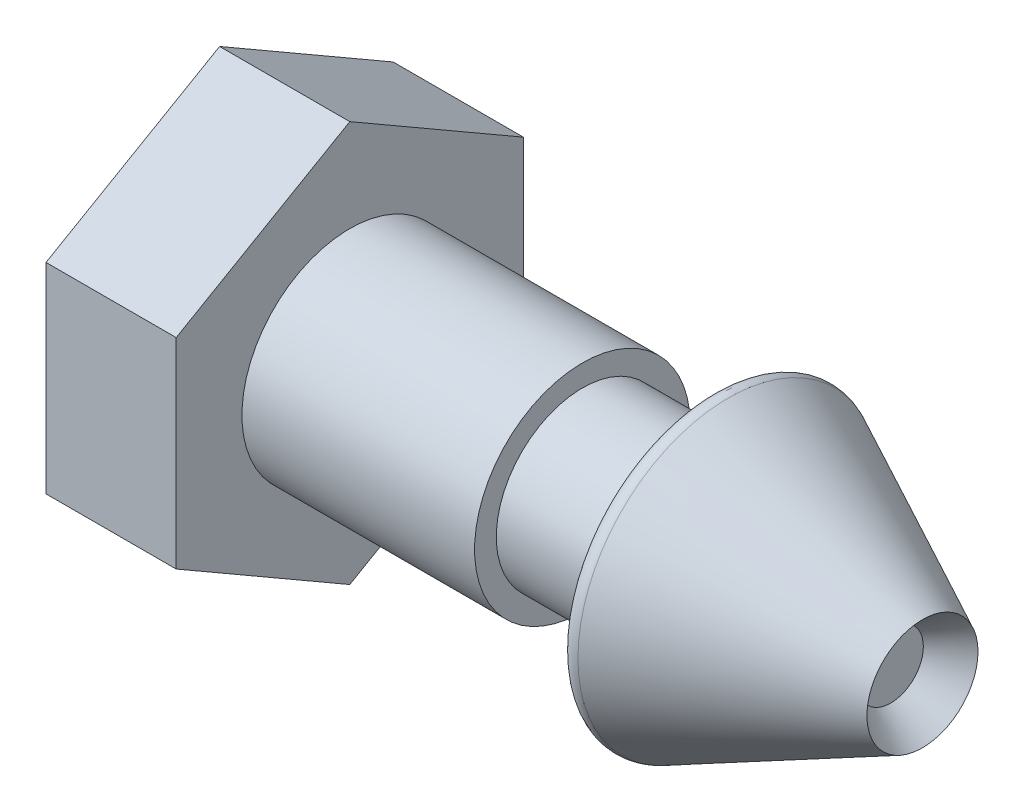
SolidWorks part; units mm, degrees
ref_plane "Front Plane" through (0, 0, 0) normal (0, 0, 1) x (1, 0, 0)
ref_plane "Top Plane" through (0, 0, 0) normal (0, 1, 0) x (1, 0, 0)
ref_plane "Right Plane" through (0, 0, 0) normal (1, 0, 0) x (0, 0, -1)
sketch "Sketch1" plane through (0, 0, 0) normal (0, 0, 1) x (1, 0, 0)
  line L0 (0, 0) -> (0, 4.97)
  line L1 (0, 4.97) -> (10.72, 4.97)
  line L2 (10.72, 4.97) -> (10.72, 3.97)
  line L3 (10.72, 3.97) -> (16.72, 3.97)
  line L4 (16.72, 3.97) -> (16.72, 7.2764)
  line L5 (16.72, 7.2764) -> (26.39, 2.56)
  line L6 (26.39, 2.56) -> (24.931, 1.5)
  line L7 (24.931, 1.5) -> (24.931, 0)
  line L8 (24.931, 0) -> (0, 0)
  point P10 (18.4758, 3.85)
  point P11 (16.8584, 1.887)
  point P12 (17.0657, -0.394)
  point P13 (0, 0)
  point P14 (26.39, 2.8408)
  point P15 (24.821, 1.7211)
  dimension "D1" = 4.97
  dimension "D2" = 10.72
  dimension "D3" = 6
  dimension "D4" = 3.97
  dimension "D5" = 26
  dimension "D6" = 9.67
  dimension "D7" = 2.56
  dimension "D8" = 36
  dimension "D9" = 1.5
revolve "Revolve1" add sketch "Sketch1" angle 360 about L8
sketch "Sketch2" plane through (0, 0, 0) normal (-1, 0, 0) x (0, 0, 1)
  line L1 (0, 9.2376) -> (-8, 4.6188)
  line L2 (-8, 4.6188) -> (-8, -4.6188)
  line L3 (-8, -4.6188) -> (0, -9.2376)
  line L4 (0, -9.2376) -> (8, -4.6188)
  line L5 (8, -4.6188) -> (8, 4.6188)
  line L6 (8, 4.6188) -> (0, 9.2376)
  circle A0 centre (0, 0) radius 8 construction
  dimension "D1" = 16
extrude "Boss-Extrude1" add sketch "Sketch2" along normal blind 6
fillet "Fillet2" radius 0.5 2 edges at (16.72, 0, -3.97) (16.72, 0, -7.2764)
